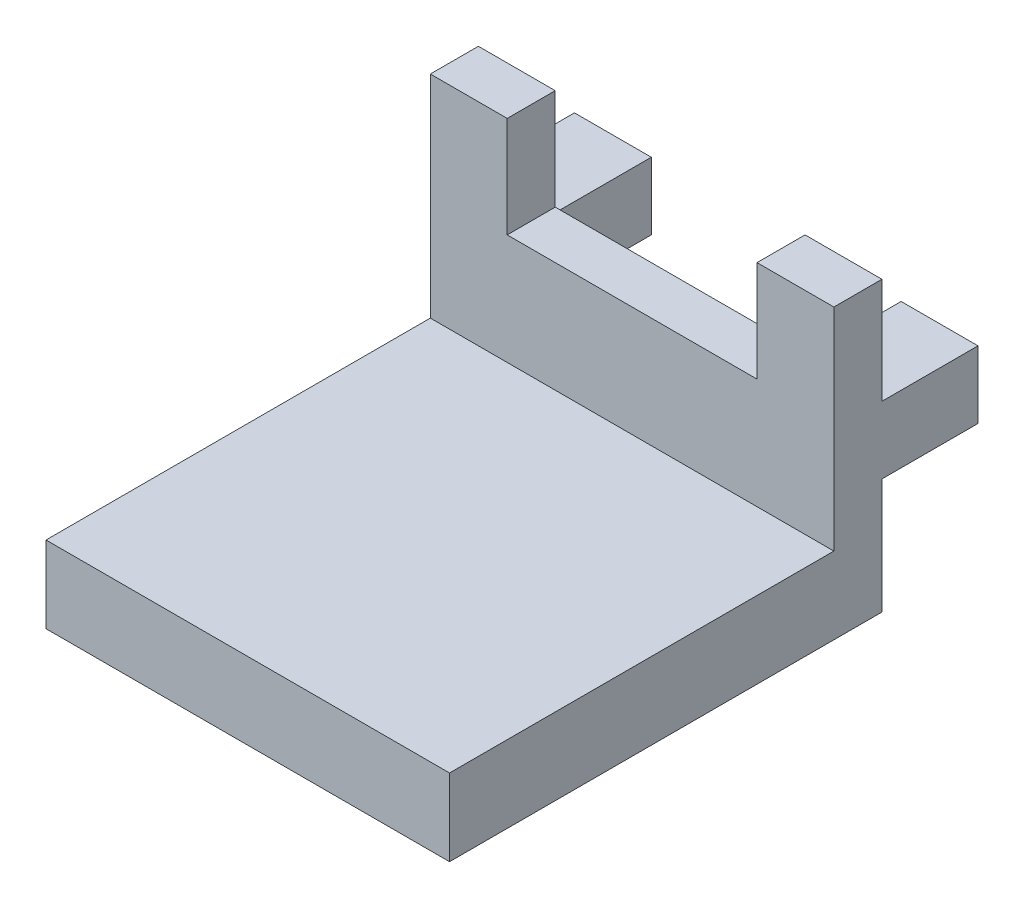
SolidWorks part; units mm, degrees
ref_plane "Front Plane" through (0, 0, 0) normal (0, 0, 1) x (1, 0, 0)
ref_plane "Top Plane" through (0, 0, 0) normal (0, 1, 0) x (1, 0, 0)
ref_plane "Right Plane" through (0, 0, 0) normal (1, 0, 0) x (0, 0, -1)
sketch "Sketch1" plane through (0, 0, 0) normal (0, 0, 1) x (1, 0, 0)
  line L5 (-17.516, -16.0395) -> (24.484, -16.0395)
  line L6 (24.484, -16.0395) -> (24.484, 13.9605)
  line L8 (-17.516, 13.9605) -> (-17.516, -16.0395)
  line L10 (16.484, 3.4605) -> (16.484, 13.9605)
  line L12 (-9.516, 13.9605) -> (-9.516, 3.4605)
  line L13 (-9.516, 3.4605) -> (16.484, 3.4605)
  line L14 (-17.516, 13.9605) -> (-9.516, 13.9605)
  line L15 (16.484, 13.9605) -> (24.484, 13.9605)
  point P2 (0, 0)
  point P4 (0, 0)
  dimension "D1" = 30
  dimension "D2" = 42
  dimension "D3" = 26
  dimension "D4" = 8
  dimension "D5" = 10.5
extrude "Boss-Extrude1" add sketch "Sketch1" along normal blind 5
sketch "Sketch2" plane through (0, 0, 0) normal (0, 0, -1) x (-1, 0, 0)
  line L10 (-24.484, -16.0395) -> (-24.484, 13.9605) construction
  line L11 (-24.484, 2.9605) -> (-16.484, 2.9605)
  line L12 (-24.484, 2.9605) -> (-24.484, -4.0395)
  line L13 (-24.484, -4.0395) -> (-16.484, -4.0395)
  line L14 (-16.484, 2.9605) -> (-16.484, -4.0395)
  line L17 (9.516, 2.9605) -> (17.516, 2.9605)
  line L18 (9.516, 2.9605) -> (9.516, -4.0395)
  line L19 (9.516, -4.0395) -> (17.516, -4.0395)
  line L20 (17.516, 2.9605) -> (17.516, -4.0395)
  line L22 (-24.484, 13.9605) -> (-16.484, 13.9605) construction
  line L23 (17.516, 13.9605) -> (17.516, -16.0395) construction
  point P0 (0, 0)
  dimension "D1" = 8
  dimension "D2" = 8
  dimension "D3" = 7
  dimension "D4" = 7
  dimension "D5" = 11
extrude "Boss-Extrude2" add sketch "Sketch2" along normal blind 10
sketch "Sketch3" plane through (0, 0, 5) normal (0, 0, 1) x (1, 0, 0)
  line L0 (24.484, -16.0395) -> (24.484, 13.9605) construction
  line L1 (-17.516, -16.0395) -> (24.484, -16.0395)
  line L2 (-17.516, -16.0395) -> (-17.516, -8.0395)
  line L3 (-17.516, -8.0395) -> (24.484, -8.0395)
  line L4 (24.484, -16.0395) -> (24.484, -8.0395)
  dimension "D1" = 8
extrude "Boss-Extrude3" add sketch "Sketch3" along normal blind 40
